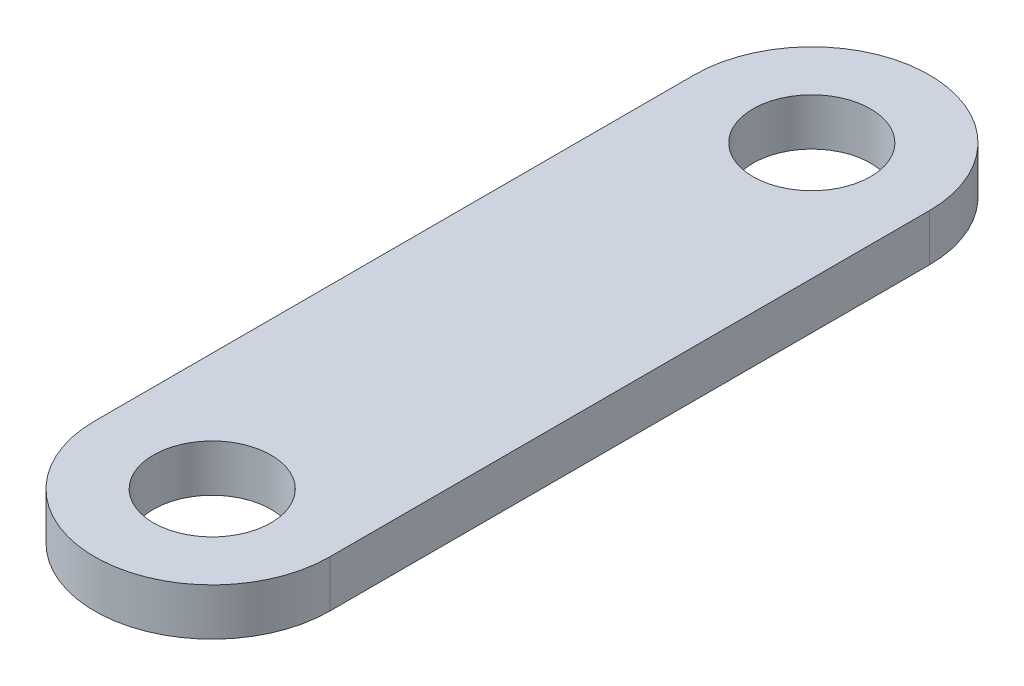
SolidWorks part; units mm, degrees
ref_plane "Front Plane" through (0, 0, 0) normal (0, 0, 1) x (1, 0, 0)
ref_plane "Top Plane" through (0, 0, 0) normal (0, 1, 0) x (1, 0, 0)
ref_plane "Right Plane" through (0, 0, 0) normal (1, 0, 0) x (0, 0, -1)
sketch "Sketch1" plane through (0, 0, 0) normal (0, 1, 0) x (1, 0, 0)
  line L1 (-50, 0) -> (-50, -255)
  line L2 (50, 0) -> (50, -255)
  arc A0 (50, 0) -> (-50, 0) centre (0, 0) ccw
  circle A1 centre (0, 0) radius 25
  circle A2 centre (0, -255) radius 25
  arc A3 (-50, -255) -> (50, -255) centre (0, -255) ccw
extrude "Boss-Extrude1" add sketch "Sketch1" along normal blind 20
